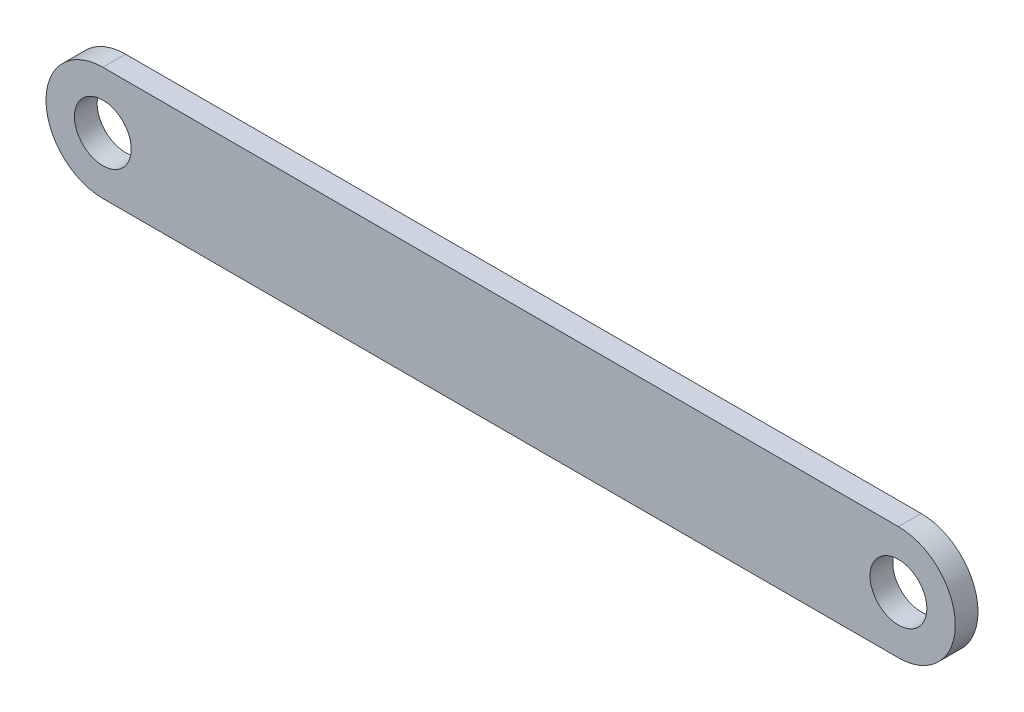
SolidWorks part; units mm, degrees
ref_plane "Front Plane" through (0, 0, 0) normal (0, 0, 1) x (1, 0, 0)
ref_plane "Top Plane" through (0, 0, 0) normal (0, 1, 0) x (1, 0, 0)
ref_plane "Right Plane" through (0, 0, 0) normal (1, 0, 0) x (0, 0, -1)
sketch "Sketch1" plane through (0, 0, 0) normal (0, 0, 1) x (1, 0, 0)
  line L0 (-52.4425, 0) -> (17.5575, 0) construction
  line L1 (-52.4425, 5) -> (17.5575, 5)
  line L2 (-52.4425, -5) -> (17.5575, -5)
  arc A0 (-52.4425, 5) -> (-52.4425, -5) centre (-52.4425, 0) ccw
  arc A1 (17.5575, -5) -> (17.5575, 5) centre (17.5575, 0) ccw
  circle A2 centre (-52.4425, 0) radius 2.5
  circle A3 centre (17.5575, 0) radius 2.5
  point P3 (-17.4425, 0)
  dimension "D1" = 70
  dimension "D2" = 10
extrude "Boss-Extrude1" add sketch "Sketch1" along normal blind 2
